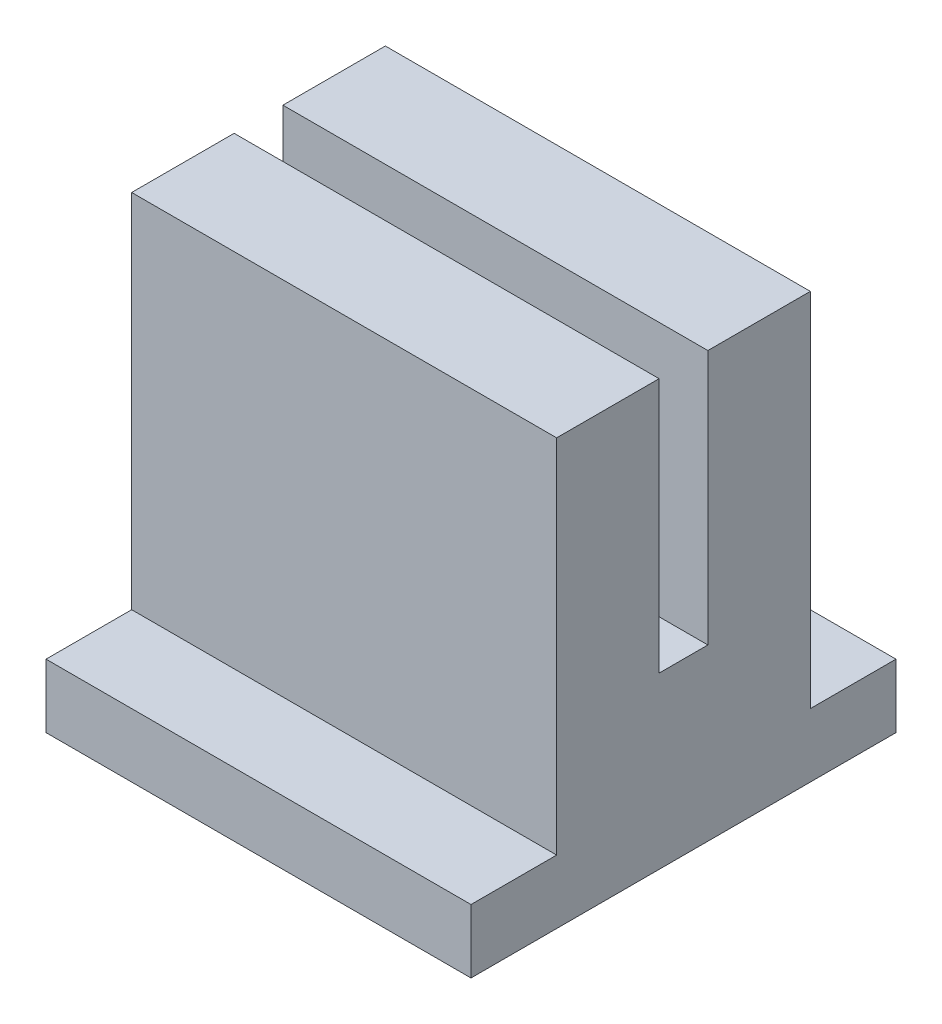
SolidWorks part; units mm, degrees
ref_plane "Front Plane" through (0, 0, 0) normal (0, 0, 1) x (1, 0, 0)
ref_plane "Top Plane" through (0, 0, 0) normal (0, 1, 0) x (1, 0, 0)
ref_plane "Right Plane" through (0, 0, 0) normal (1, 0, 0) x (0, 0, -1)
sketch "Sketch7" plane through (0, 0, 0) normal (1, 0, 0) x (0, 0, -1)
  line L0 (0, 0) -> (0, -7.4879)
  line L1 (0, -7.4879) -> (50, -7.4879)
  line L2 (50, -7.4879) -> (50, 0)
  line L3 (50, 0) -> (39.9237, 0)
  line L4 (39.9237, 0) -> (39.9237, 42.5121)
  line L5 (39.9237, 42.5121) -> (27.8683, 42.5121)
  line L6 (27.8683, 42.5121) -> (27.8683, 12.5121)
  line L7 (27.8683, 12.5121) -> (22.1317, 12.5121)
  line L8 (22.1317, 12.5121) -> (22.1317, 42.5121)
  line L9 (22.1317, 42.5121) -> (10.0763, 42.5121)
  line L10 (10.0763, 42.5121) -> (10.0763, 0)
  line L11 (10.0763, 0) -> (0, 0)
  point P3 (3.6317, 0)
  point P14 (9.6776, 0)
  dimension "D1" = 50
  dimension "D2" = 50
  dimension "D3" = 30
extrude "Boss-Extrude5" add sketch "Sketch7" along normal blind 50
